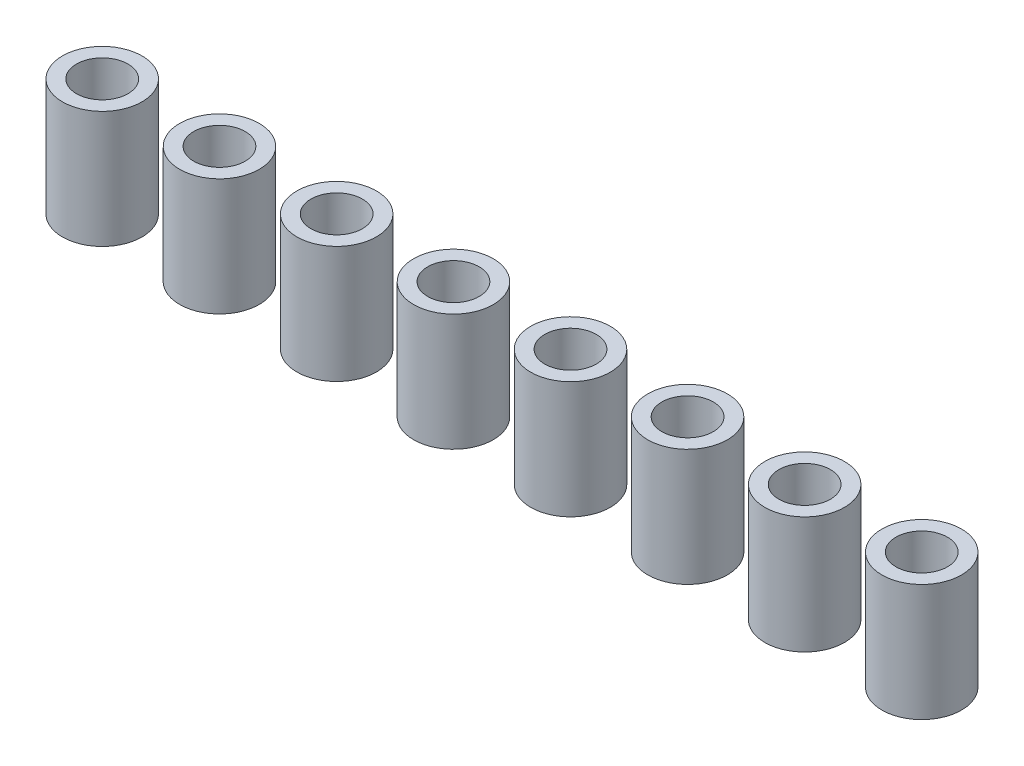
SolidWorks part; units mm, degrees
ref_plane "Front Plane" through (0, 0, 0) normal (0, 0, 1) x (1, 0, 0)
ref_plane "Top Plane" through (0, 0, 0) normal (0, 1, 0) x (1, 0, 0)
ref_plane "Right Plane" through (0, 0, 0) normal (1, 0, 0) x (0, 0, -1)
sketch "Sketch1" plane through (0, 0, 0) normal (0, 1, 0) x (1, 0, 0)
  line L0 (-55, 0) -> (55, 0) construction
  circle A1 centre (0, 0) radius 1.7
  circle A2 centre (0, 0) radius 1.1
  circle A3 centre (5, 0.0071) radius 1.7
  circle A4 centre (5, 0.0071) radius 1.1
  circle A5 centre (10, 0.0122) radius 1.7
  circle A6 centre (10, 0.0122) radius 1.1
  circle A7 centre (15, 0) radius 1.7
  circle A8 centre (15, 0) radius 1.1
  circle A9 centre (20, 0) radius 1.7
  circle A10 centre (20, 0) radius 1.1
  circle A11 centre (25, 0) radius 1.7
  circle A12 centre (25, 0) radius 1.1
  circle A13 centre (30, 0) radius 1.7
  circle A14 centre (30, 0) radius 1.1
  circle A15 centre (35, 0) radius 1.7
  circle A16 centre (35, 0) radius 1.1
  point P25 (15, 0)
  point P28 (20, 0)
  point P29 (30, 0)
  point P30 (35, 0)
  point P31 (25, 0)
  dimension "D1" = 2.2
  dimension "D2" = 3.4
  dimension "D3" = 2.2
  dimension "D4" = 3.4
  dimension "D5" = 2.2
  dimension "D6" = 3.4
  dimension "D7" = 2.2
  dimension "D8" = 3.4
  dimension "D9" = 2.2
  dimension "D10" = 3.4
  dimension "D11" = 2.2
  dimension "D12" = 3.4
  dimension "D13" = 2.2
  dimension "D14" = 3.4
  dimension "D15" = 2.2
  dimension "D16" = 3.4
  dimension "D17" = 5
  dimension "D18" = 5
  dimension "D19" = 5
  dimension "D20" = 5
  dimension "D21" = 5
  dimension "D22" = 5
  dimension "D23" = 5
extrude "Boss-Extrude1" add sketch "Sketch1" along normal blind 5
